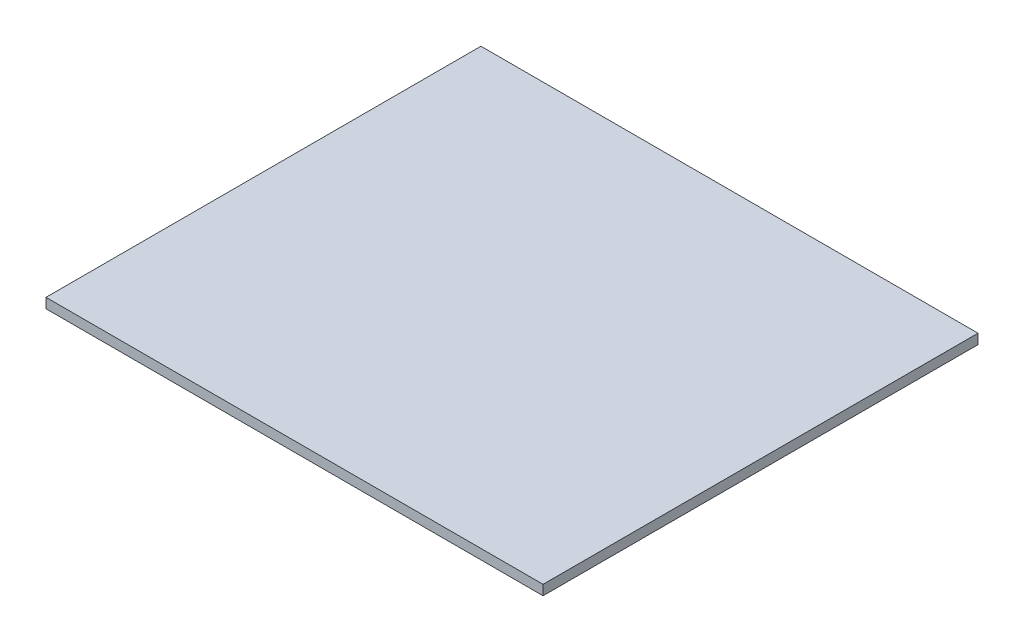
SolidWorks part; units mm, degrees
ref_plane "Front Plane" through (0, 0, 0) normal (0, 0, 1) x (1, 0, 0)
ref_plane "Top Plane" through (0, 0, 0) normal (0, 1, 0) x (1, 0, 0)
ref_plane "Right Plane" through (0, 0, 0) normal (1, 0, 0) x (0, 0, -1)
sketch "Sketch1" plane through (0, 0, 0) normal (0, 1, 0) x (1, 0, 0)
  line L1 (0, 0) -> (80, 0)
  line L2 (0, 0) -> (0, 70)
  line L3 (0, 70) -> (80, 70)
  line L4 (80, 0) -> (80, 70)
  dimension "D1" = 80
  dimension "D2" = 70
extrude "Boss-Extrude1" add sketch "Sketch1" along normal blind 1.6
